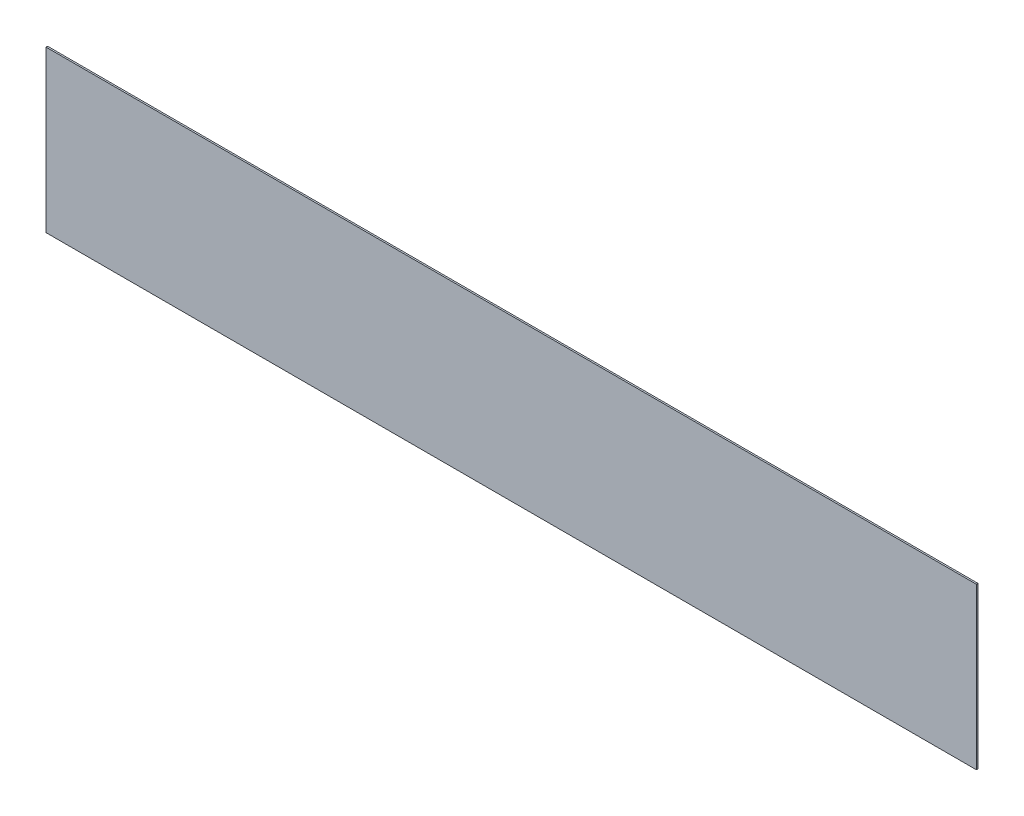
SolidWorks part; units mm, degrees
ref_plane "Front Plane" through (0, 0, 0) normal (0, 0, 1) x (1, 0, 0)
ref_plane "Top Plane" through (0, 0, 0) normal (0, 1, 0) x (1, 0, 0)
ref_plane "Right Plane" through (0, 0, 0) normal (1, 0, 0) x (0, 0, -1)
other "Configuration Table"
sketch "Sketch1" plane through (0, 0, 0) normal (0, 0, 1) x (1, 0, 0)
  line L1 (13.7, 4) -> (604.3, 4)
  line L2 (13.7, 4) -> (13.7, 106)
  line L3 (13.7, 106) -> (604.3, 106)
  line L4 (604.3, 4) -> (604.3, 106)
extrude "CEK_icecek_kutu_arka_1.0_1" add sketch "Sketch1" against normal blind 1 from offset 699 separate body
